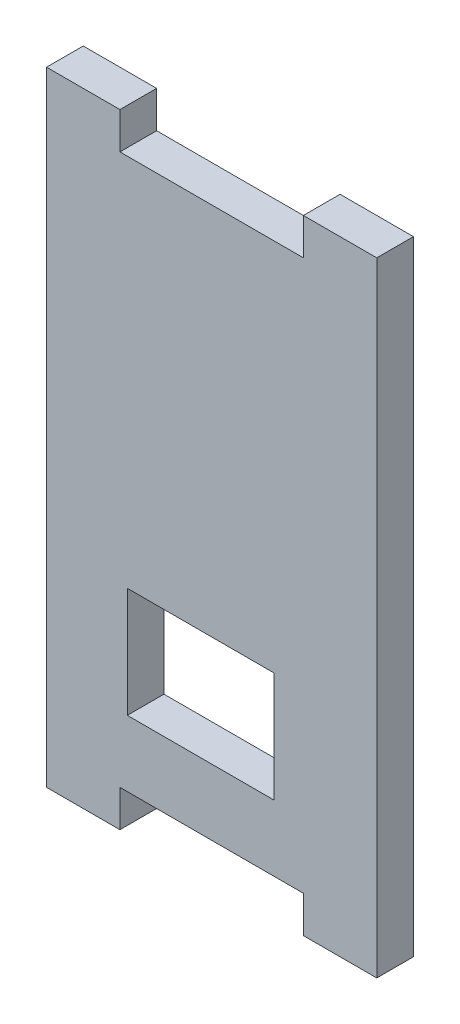
SolidWorks part; units mm, degrees
ref_plane "Plan de face" through (0, 0, 0) normal (0, 0, 1) x (1, 0, 0)
ref_plane "Plan de dessus" through (0, 0, 0) normal (0, 1, 0) x (1, 0, 0)
ref_plane "Plan de droite" through (0, 0, 0) normal (1, 0, 0) x (0, 0, -1)
sketch "Esquisse1" plane through (0, 0, 0) normal (0, 0, 1) x (1, 0, 0)
  line L1 (0, 0) -> (45, 0)
  line L2 (0, 0) -> (0, 75)
  line L3 (0, 75) -> (45, 75)
  line L4 (45, 0) -> (45, 75)
  line L5 (11, 24) -> (31, 24)
  line L6 (11, 24) -> (11, 9)
  line L7 (11, 9) -> (31, 9)
  line L8 (31, 24) -> (31, 9)
  dimension "D1" = 75
  dimension "D2" = 45
  dimension "D3" = 20
  dimension "D4" = 15
  dimension "D5" = 9
  dimension "D6" = 11
extrude "Boss.-Extru.1" add sketch "Esquisse1" along normal blind 5
sketch "Esquisse2" plane through (0, 0, 5) normal (0, 0, 1) x (1, 0, 0)
  line L1 (0, 75) -> (10, 75)
  line L2 (0, 75) -> (0, 80)
  line L3 (0, 80) -> (10, 80)
  line L4 (10, 75) -> (10, 80)
  line L5 (45, 75) -> (35, 75)
  line L6 (45, 75) -> (45, 80)
  line L7 (45, 80) -> (35, 80)
  line L8 (35, 75) -> (35, 80)
  line L9 (0, 0) -> (10, 0)
  line L10 (0, 0) -> (0, -5)
  line L11 (0, -5) -> (10, -5)
  line L12 (10, 0) -> (10, -5)
  line L13 (45, 0) -> (35, 0)
  line L14 (45, 0) -> (45, -5)
  line L15 (45, -5) -> (35, -5)
  line L16 (35, 0) -> (35, -5)
  dimension "D1" = 10
  dimension "D2" = 5
extrude "Boss.-Extru.2" add sketch "Esquisse2" against normal blind 5
